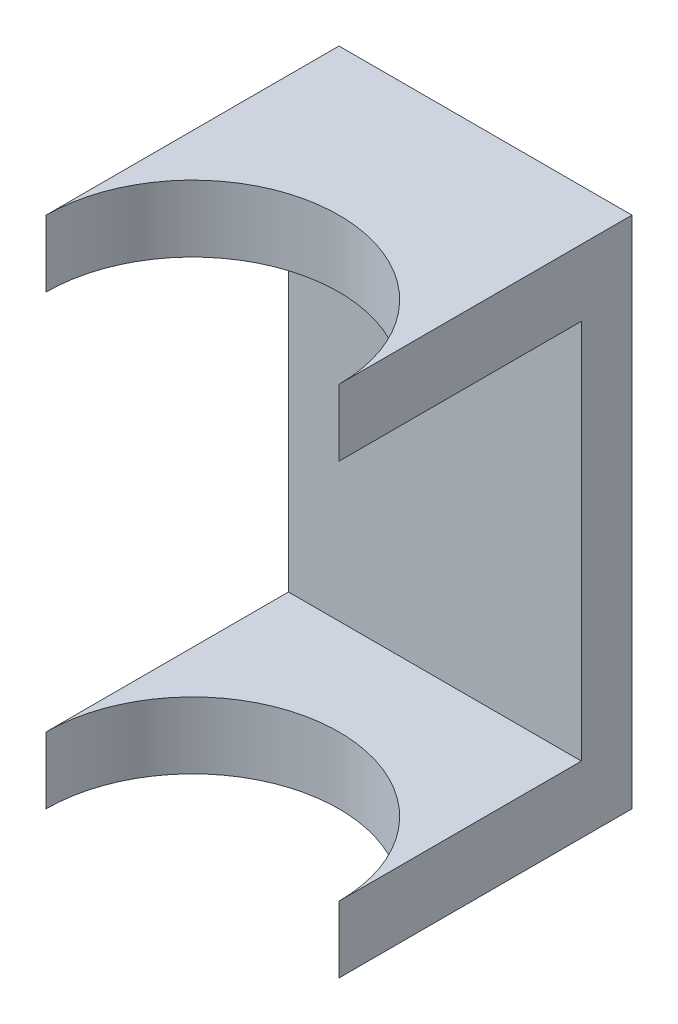
SolidWorks part; units mm, degrees
ref_plane "Front Plane" through (0, 0, 0) normal (0, 0, 1) x (1, 0, 0)
ref_plane "Top Plane" through (0, 0, 0) normal (0, 1, 0) x (1, 0, 0)
ref_plane "Right Plane" through (0, 0, 0) normal (1, 0, 0) x (0, 0, -1)
sketch "Sketch1" plane through (0, 0, 0) normal (0, 1, 0) x (1, 0, 0)
  line L1 (-46.657, 26.2778) -> (12.525, 26.2778)
  line L2 (-46.657, 26.2778) -> (-46.657, -32.9042)
  line L3 (-46.657, -32.9042) -> (12.525, -32.9042)
  line L4 (12.525, 26.2778) -> (12.525, -32.9042)
  dimension "D1" = 59.182
  dimension "D2" = 59.182
extrude "Boss-Extrude2" add sketch "Sketch1" along normal blind 103.886
sketch "Sketch4" plane through (0, 0, 0) normal (0, -1, 0) x (1, 0, 0)
  line L0 (-46.657, 32.9042) -> (12.525, 32.9042) construction
  circle A0 centre (-17.066, 32.9042) radius 29.591
extrude "Cut-Extrude1" cut sketch "Sketch4" against normal through all
sketch "Sketch6" plane through (0, 0, -26.2778) normal (0, 0, -1) x (-1, 0, 0)
  line L0 (-12.525, 103.886) -> (-12.525, 0) construction
  line L1 (-12.525, 90.424) -> (46.657, 90.424)
  line L2 (-12.525, 90.424) -> (-12.525, 13.462)
  line L3 (-12.525, 13.462) -> (46.657, 13.462)
  line L4 (46.657, 90.424) -> (46.657, 13.462)
  line L5 (46.657, 103.886) -> (46.657, 0) construction
  dimension "D1" = 76.962
extrude "Cut-Extrude2" cut sketch "Sketch6" against normal through all
sketch "Sketch8" plane through (0, 90.424, 0) normal (0, -1, 0) x (1, 0, 0)
  line L0 (-46.657, 32.9042) -> (-46.657, -26.2778) construction
  line L1 (-46.657, -16.072) -> (12.525, -16.072)
  line L2 (-46.657, -16.072) -> (-46.657, -26.2778)
  line L3 (-46.657, -26.2778) -> (12.525, -26.2778)
  line L4 (12.525, -16.072) -> (12.525, -26.2778)
  line L5 (12.525, 32.9042) -> (12.525, -26.2778) construction
  line L6 (-46.657, -26.2778) -> (12.525, -26.2778) construction
extrude "Boss-Extrude3" add sketch "Sketch8" along normal blind 76.962
